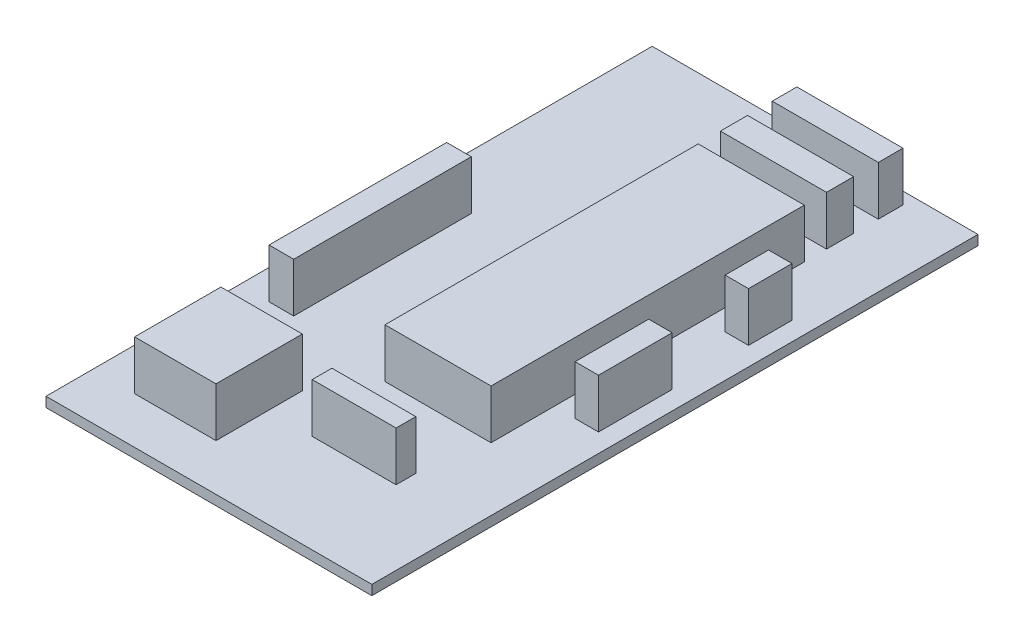
SolidWorks part; units mm, degrees
ref_plane "Alzado" through (0, 0, 0) normal (0, 0, 1) x (1, 0, 0)
ref_plane "Planta" through (0, 0, 0) normal (0, 1, 0) x (1, 0, 0)
ref_plane "Vista lateral" through (0, 0, 0) normal (1, 0, 0) x (0, 0, -1)
sketch "Croquis2" plane through (0, 0, 0) normal (0, 1, 0) x (1, 0, 0)
  line L1 (-26.5, 49.3) -> (26.5, 49.3)
  line L2 (-26.5, 49.3) -> (-26.5, -49.3)
  line L3 (-26.5, -49.3) -> (26.5, -49.3)
  line L4 (26.5, 49.3) -> (26.5, -49.3)
  line L5 (-26.5, 49.3) -> (26.5, -49.3) construction
  line L6 (-26.5, -49.3) -> (26.5, 49.3) construction
  point P0 (0, 0)
  dimension "D1" = 53
  dimension "D2" = 98.6
extrude "Saliente-Extruir1" add sketch "Croquis2" along normal blind 1.6
sketch "Croquis3" plane through (0, 1.6, 0) normal (0, 1, 0) x (1, 0, 0)
  line L0 (26.5, -49.3) -> (26.5, 49.3) construction
  line L1 (-1.0031, 31.2956) -> (16.2497, 31.2956)
  line L2 (-1.0031, 31.2956) -> (-1.0031, -19.6601)
  line L3 (-1.0031, -19.6601) -> (16.2497, -19.6601)
  line L4 (16.2497, 31.2956) -> (16.2497, -19.6601)
  line L5 (-1.0031, 31.2956) -> (16.2497, -19.6601) construction
  line L6 (-1.0031, -19.6601) -> (16.2497, 31.2956) construction
  line L7 (-19.6601, -27.6846) -> (-6.4196, -27.6846)
  line L8 (-19.6601, -27.6846) -> (-19.6601, -41.7275)
  line L9 (-19.6601, -41.7275) -> (-6.4196, -41.7275)
  line L10 (-6.4196, -27.6846) -> (-6.4196, -41.7275)
  line L11 (-19.6601, -27.6846) -> (-6.4196, -41.7275) construction
  line L12 (-19.6601, -41.7275) -> (-6.4196, -27.6846) construction
  line L13 (-21.6662, -17.8546) -> (-17.6539, -17.8546)
  line L14 (-21.6662, -17.8546) -> (-21.6662, 11.0337)
  line L15 (-21.6662, 11.0337) -> (-17.6539, 11.0337)
  line L16 (-17.6539, -17.8546) -> (-17.6539, 11.0337)
  line L17 (-21.6662, -17.8546) -> (-17.6539, 11.0337) construction
  line L18 (-21.6662, 11.0337) -> (-17.6539, -17.8546) construction
  line L19 (-1.0031, 47.3447) -> (16.2497, 47.3447)
  line L20 (-1.0031, 47.3447) -> (-1.0031, 43.3324)
  line L21 (-1.0031, 43.3324) -> (16.2497, 43.3324)
  line L22 (16.2497, 47.3447) -> (16.2497, 43.3324)
  line L23 (-1.0031, 47.3447) -> (16.2497, 43.3324) construction
  line L24 (-1.0031, 43.3324) -> (16.2497, 47.3447) construction
  line L25 (16.2497, 39.3201) -> (-1.0031, 39.3201)
  line L26 (16.2497, 39.3201) -> (16.2497, 34.9067)
  line L27 (16.2497, 34.9067) -> (-1.0031, 34.9067)
  line L28 (-1.0031, 39.3201) -> (-1.0031, 34.9067)
  line L29 (16.2497, 39.3201) -> (-1.0031, 34.9067) construction
  line L30 (16.2497, 34.9067) -> (-1.0031, 39.3201) construction
  line L31 (19.6625, 14.9999) -> (23.4717, 14.9999)
  line L32 (19.6625, 14.9999) -> (19.6625, 22.0674)
  line L33 (19.6625, 22.0674) -> (23.4717, 22.0674)
  line L34 (23.4717, 14.9999) -> (23.4717, 22.0674)
  line L35 (19.6625, 14.9999) -> (23.4717, 22.0674) construction
  line L36 (19.6625, 22.0674) -> (23.4717, 14.9999) construction
  line L37 (19.6625, 2.5801) -> (23.4717, 2.5801)
  line L38 (19.6625, 2.5801) -> (19.6625, -9.4009)
  line L39 (19.6625, -9.4009) -> (23.4717, -9.4009)
  line L40 (23.4717, 2.5801) -> (23.4717, -9.4009)
  line L41 (19.6625, 2.5801) -> (23.4717, -9.4009) construction
  line L42 (19.6625, -9.4009) -> (23.4717, 2.5801) construction
  line L43 (0.8025, -30.092) -> (14.4441, -30.092)
  line L44 (0.8025, -30.092) -> (0.8025, -33.3018)
  line L45 (0.8025, -33.3018) -> (14.4441, -33.3018)
  line L46 (14.4441, -30.092) -> (14.4441, -33.3018)
  line L47 (0.8025, -30.092) -> (14.4441, -33.3018) construction
  line L48 (0.8025, -33.3018) -> (14.4441, -30.092) construction
  point P0 (7.6233, 5.8178)
  point P5 (-13.0398, -34.7061)
  point P10 (-19.6601, -3.4104)
  point P15 (7.6233, 45.3385)
  point P20 (7.6233, 37.1134)
  point P25 (21.5671, 18.5337)
  point P30 (21.5671, -3.4104)
  point P35 (7.6233, -31.6969)
  dimension "D1" = 3.0283
  dimension "D2" = 4.9329
  dimension "D3" = 6.8375
  dimension "D4" = 10.2503
  dimension "D5" = 12.0559
  dimension "D6" = 18.8767
  dimension "D7" = 25.6975
  dimension "D8" = 27.5031
  dimension "D9" = 32.9196
  dimension "D10" = 39.5398
  dimension "D11" = 44.1539
  dimension "D12" = 46.1601
  dimension "D13" = 48.1662
  dimension "D14" = 1.9553
  dimension "D15" = 9.9799
  dimension "D16" = 12.1866
  dimension "D17" = 18.0044
  dimension "D18" = 27.2326
  dimension "D19" = 30.7663
  dimension "D20" = 38.2663
  dimension "D21" = 43.4822
  dimension "D22" = 76.9846
  dimension "D23" = 79.392
extrude "Saliente-Extruir2" add sketch "Croquis3" along normal blind 8
